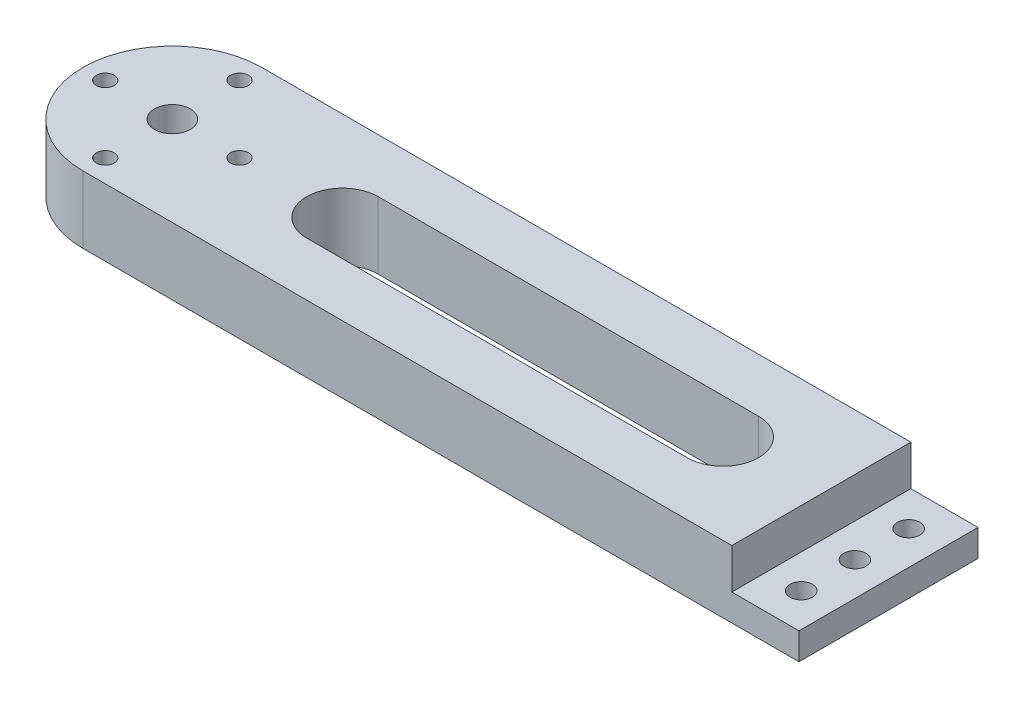
SolidWorks part; units mm, degrees
ref_plane "Front" through (0, 0, 0) normal (0, 0, 1) x (1, 0, 0)
ref_plane "Top" through (0, 0, 0) normal (0, 1, 0) x (1, 0, 0)
ref_plane "Right" through (0, 0, 0) normal (1, 0, 0) x (0, 0, -1)
sketch "草图1" plane through (0, 0, 0) normal (0, 1, 0) x (1, 0, 0)
  line L1 (0, 20) -> (160, 20)
  line L2 (0, 20) -> (0, -20) construction
  line L3 (0, -20) -> (160, -20)
  line L4 (160, 20) -> (160, -20)
  arc A0 (0, 20) -> (0, -20) centre (0, 0) ccw
  circle A1 centre (0, 15) radius 2
  circle A2 centre (15, 0) radius 2
  circle A3 centre (0, -15) radius 2
  circle A4 centre (-15, 0) radius 2
  circle A5 centre (0, 0) radius 4
  point P17 (0, 0)
  dimension "D1" = 20
  dimension "D4" = 4
  dimension "D6" = 8
  dimension "D2" = 15
  dimension "D3" = 160
  dimension "D5" = 4
extrude "凸台-拉伸1" add sketch "草图1" along normal blind 15
sketch "草图2" plane through (0, 0, 20) normal (0, 0, 1) x (1, 0, 0)
  line L1 (160, 15) -> (145, 15)
  line L2 (160, 15) -> (160, 6)
  line L3 (160, 6) -> (145, 6)
  line L4 (145, 15) -> (145, 6)
  dimension "D1" = 15
  dimension "D2" = 9
extrude "切除-拉伸1" cut sketch "草图2" against normal up to next
sketch "草图3" plane through (0, 0, 0) normal (0, -1, 0) x (1, 0, 0)
  line L0 (152.5, 27.1546) -> (152.5, -33.3658) construction
  line L1 (160, 20) -> (160, -20) construction
  line L2 (138.6735, 0) -> (169.0143, 0) construction
  point P7 (152.5, 0)
  point P9 (152.5, 12)
  point P10 (152.5, -12)
  dimension "D1" = 7.5
  dimension "D2" = 12
hole_wizard "Ø5.0 (5) 直径孔1" positions "草图4" profile "草图5" hole size "Ø5.0" standard "GB" end condition through all
sketch "草图4" plane through (0, 0, 0) normal (0, -1, 0) x (-1, 0, 0)
  point P0 (-152.5, -12)
  point P3 (-152.5, 0)
  point P6 (-152.5, 12)
sketch "草图5" plane through (152.5, 0, 12) normal (1, 0, 0) x (0, 0, -1)
  line L0 (0, 0) -> (0, 15)
  line L1 (0, 15) -> (2.5, 15)
  line L2 (2.5, 15) -> (2.5, 0)
  line L5 (2.5, 0) -> (0, 0)
  line L11 (0, -6.35) -> (0, 107.95) construction
  dimension "通孔孔直径" = 5
  dimension "通孔孔深度" = 15
sketch "草图6" plane through (0, 0, 0) normal (0, 1, 0) x (1, 0, 0)
  line L0 (-24.9853, 0) -> (181.7074, 0) construction
  line L2 (38, -8) -> (123, -8)
  line L3 (38, -8) -> (38, 8) construction
  line L4 (38, 8) -> (123, 8)
  line L5 (123, -8) -> (123, 8) construction
  line L6 (38, -8) -> (123, 8) construction
  line L7 (38, 8) -> (123, -8) construction
  line L8 (145, 20) -> (145, -20) construction
  arc A0 (38, 8) -> (38, -8) centre (38, 0) ccw
  arc A1 (123, 8) -> (123, -8) centre (123, 0) cw
  point P3 (80.5, 0)
  point P9 (83.5341, 0)
  dimension "D1" = 16
  dimension "D2" = 38
  dimension "D3" = 22
extrude "切除-拉伸2" cut sketch "草图6" along normal up to next
